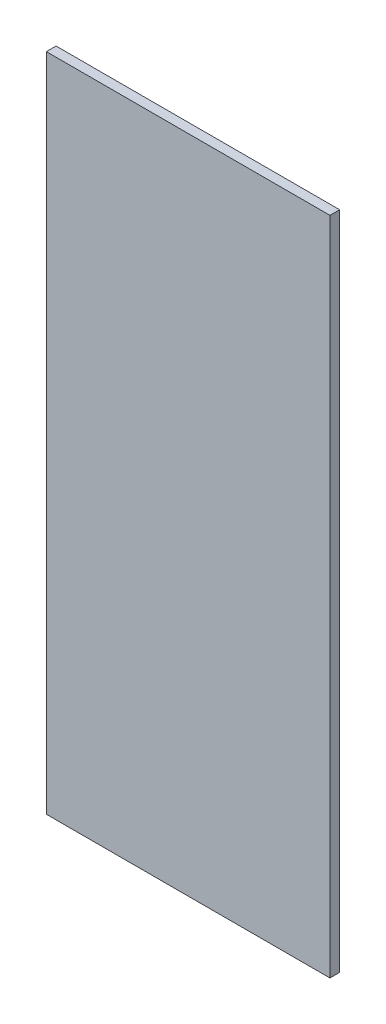
SolidWorks part; units mm, degrees
material "PC High Viscosity"
ref_plane "Front Plane" through (0, 0, 0) normal (0, 0, 1) x (1, 0, 0)
ref_plane "Top Plane" through (0, 0, 0) normal (0, 1, 0) x (1, 0, 0)
ref_plane "Right Plane" through (0, 0, 0) normal (1, 0, 0) x (0, 0, -1)
sketch "Sketch1" plane through (0, 0, 0) normal (0, 0, 1) x (1, 0, 0)
  line L1 (-73, -170) -> (73, -170)
  line L2 (-73, -170) -> (-73, 170)
  line L3 (-73, 170) -> (73, 170)
  line L4 (73, -170) -> (73, 170)
  line L5 (-73, -170) -> (73, 170) construction
  line L6 (-73, 170) -> (73, -170) construction
  point P0 (0, 0)
  dimension "D1" = 146
  dimension "D2" = 340
extrude "Boss-Extrude1" add sketch "Sketch1" along normal mid plane 5
